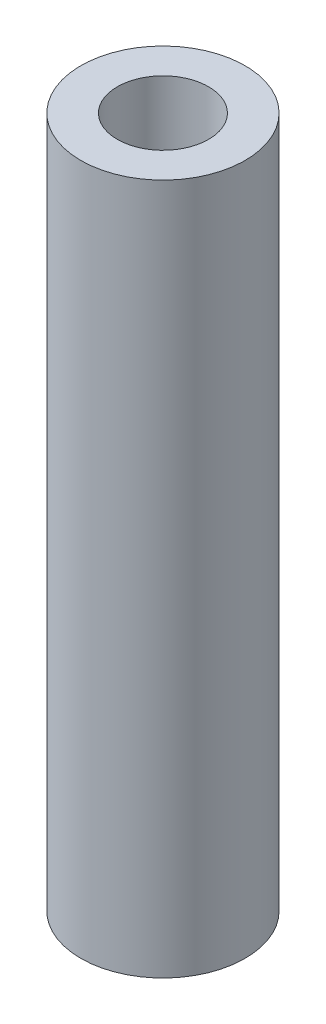
SolidWorks part; units mm, degrees
material "EPDM"
ref_plane "Płaszczyzna przednia" through (0, 0, 0) normal (0, 0, 1) x (1, 0, 0)
ref_plane "Płaszczyzna górna" through (0, 0, 0) normal (0, 1, 0) x (1, 0, 0)
ref_plane "Płaszczyzna prawa" through (0, 0, 0) normal (1, 0, 0) x (0, 0, -1)
sketch "Szkic1" plane through (0, 0, 0) normal (0, 0, 1) x (1, 0, 0)
  line L0 (0, 344.7443) -> (0, -336.9732) construction
  line L1 (35, 265) -> (63, 265)
  line L2 (35, 265) -> (35, -265)
  line L3 (35, -265) -> (63, -265)
  line L4 (63, 265) -> (63, -265)
  point P4 (35, 0)
  dimension "D1" = 63
  dimension "D2" = 35
  dimension "D3" = 530
revolve "Obrót1" add sketch "Szkic1" angle 360 about L0
